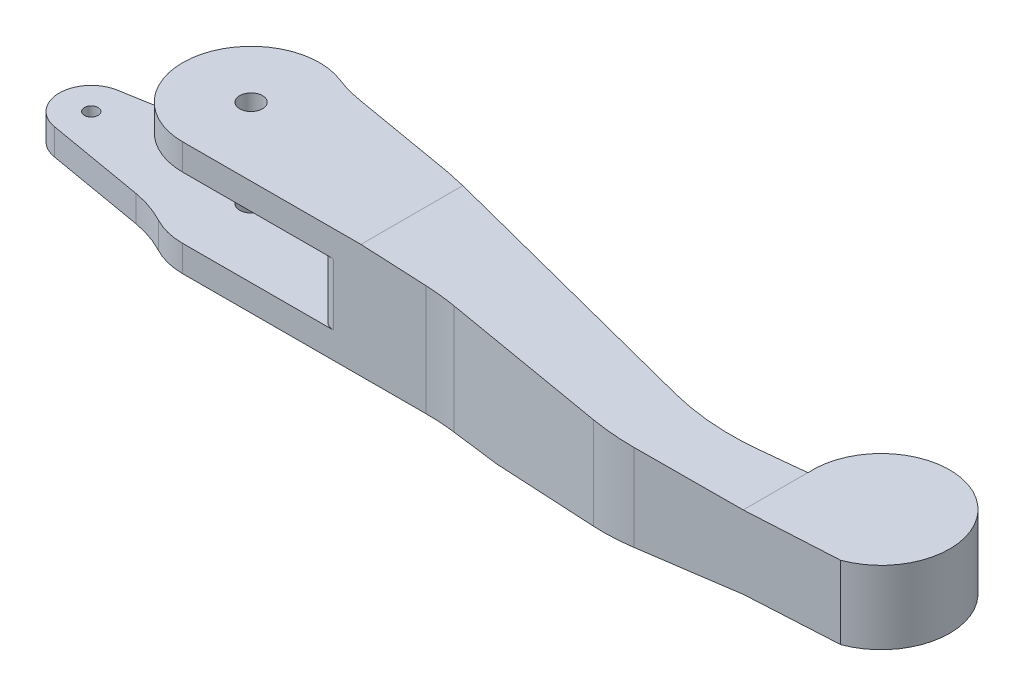
SolidWorks part; units mm, degrees
ref_plane "Front Plane" through (0, 0, 0) normal (0, 0, 1) x (1, 0, 0)
ref_plane "Top Plane" through (0, 0, 0) normal (0, 1, 0) x (1, 0, 0)
ref_plane "Right Plane" through (0, 0, 0) normal (1, 0, 0) x (0, 0, -1)
other "Graphic1"
other "Graphic (Closed) -1"
sketch "Sketch1" plane through (0, 0, 0) normal (0, 1, 0) x (1, 0, 0)
  line L0 (0.0258, -15) -> (53.1997, -14.9086)
  line L1 (59.696, -15.3212) -> (94.8143, -19.8611)
  line L2 (104.0157, -20.1958) -> (146.8594, -17.8005)
  line L4 (126.6854, -4.7826) -> (117.2146, -6.293)
  line L5 (98.6048, -5.7509) -> (35.8498, 8.0449)
  line L6 (33.6184, 8.4825) -> (7.5, 12.9904)
  line L7 (0, 0) -> (7.5, 12.9904) construction
  line L8 (126.6854, -4.7826) -> (146.8594, -17.8005) construction
  arc A0 (7.5, 12.9904) -> (0.0258, -15) centre (0, 0) ccw
  circle A1 centre (0, 0) radius 2.5
  arc A2 (35.8498, 8.0449) -> (33.6184, 8.4825) centre (25.1144, -40.789) ccw
  arc A3 (117.2146, -6.293) -> (98.6048, -5.7509) centre (109.3402, 43.083) cw
  arc A4 (94.8143, -19.8611) -> (104.0157, -20.1958) centre (101.2247, 29.7262) ccw
  arc A5 (53.1997, -14.9086) -> (59.696, -15.3212) centre (53.2856, -64.9086) cw
  arc A6 (126.6854, -4.7826) -> (146.8594, -17.8005) centre (141.6488, -3.7346) cw
  point P14 (34.7391, 8.289)
  point P18 (107.8583, -7.7851)
  point P23 (99.3995, -20.4539)
  point P28 (56.4613, -14.903)
  dimension "D1" = 15
  dimension "D2" = 5
  dimension "D5" = 50
  dimension "D6" = 15
  dimension "D3" = 12.6687
  dimension "D4" = 150
extrude "Boss-Extrude1" add sketch "Sketch1" along normal mid plane 25
sketch "Sketch2" plane through (0, 0, 0) normal (0, 0, 1) x (1, 0, 0)
  line L2 (38.9809, -15) -> (126.6488, -8)
  line L3 (156.6488, 8) -> (156.6488, 12.5)
  line L4 (156.6488, 12.5) -> (38.9809, 12.5)
  line L5 (38.9809, -15) -> (156.6488, -15)
  line L6 (156.6488, -15) -> (156.6488, -8)
  line L8 (156.6488, -12.5) -> (156.6488, 12.5) construction
  line L9 (126.6488, -8) -> (156.6488, -8)
  line L10 (38.9809, 12.5) -> (126.6488, 8)
  line L11 (126.6488, 8) -> (156.6488, 8)
  line L12 (126.6488, 12.5) -> (126.6488, -12.5) construction
  dimension "D1" = 16
  dimension "D2" = 7
extrude "Cut-Extrude1" cut sketch "Sketch2" against normal up to next and the other way up to next
fillet "Fillet1" radius 30 1 edges at (7.5, 0, -12.9904)
sketch "Sketch3" plane through (0, 0, 0) normal (0, 0, 1) x (1, 0, 0)
  line L0 (-15, 12.5) -> (-15, -12.5) construction
  line L1 (-15, -6.75) -> (30, -6.75)
  line L2 (-15, -6.75) -> (-15, 6.75)
  line L3 (-15, 6.75) -> (30, 6.75)
  line L4 (30, -6.75) -> (30, 6.75)
  point P4 (-15, 0)
  dimension "D1" = 45
  dimension "D2" = 13.5
extrude "Cut-Extrude2" cut sketch "Sketch3" against normal up to next and the other way up to next
fillet "Fillet2" radius 3 2 edges at (30, 0, 14.9485) (30, 0, -9.107)
sketch "Sketch4" plane through (0, 12.5, 0) normal (0, 1, 0) x (1, 0, 0)
  line L0 (-9.6307, 11.5) -> (-36.1951, 6.8972)
  line L1 (-36.1951, -6.8972) -> (-9.6307, -11.5)
  arc A0 (5.4778, 13.964) -> (0.0258, -15) centre (0, 0) ccw construction
  arc A1 (-36.1951, 6.8972) -> (-36.1951, -6.8972) centre (-35, 0) ccw
  arc A2 (-9.6307, 11.5) -> (-9.6307, -11.5) centre (0, 0) ccw
  circle A3 centre (-35, 0) radius 1.5
  dimension "D1" = 3
  dimension "D2" = 7
  dimension "D3" = 35
  dimension "D4" = 23
extrude "Boss-Extrude2" add sketch "Sketch4" along normal up to surface (5.75 mm away) from surface at -25 up to face at (17.7865, -6.75, -0.2557) starting at face at (0, -12.5, 2.5)
fillet "Fillet3" radius 25 2 edges at (-9.6307, -9.625, 11.5) (-9.6307, -9.625, -11.5)
